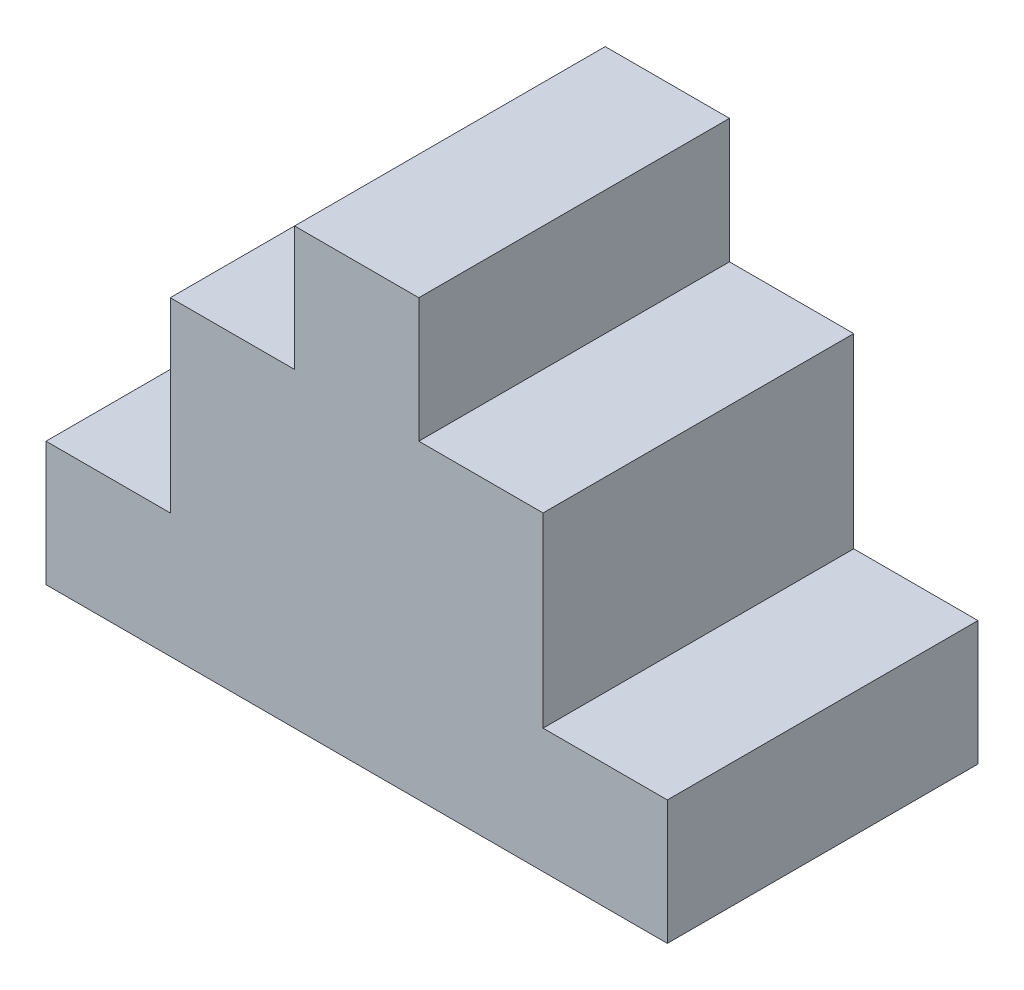
SolidWorks part; units mm, degrees
ref_plane "Front Plane" through (0, 0, 0) normal (0, 0, 1) x (1, 0, 0)
ref_plane "Top Plane" through (0, 0, 0) normal (0, 1, 0) x (1, 0, 0)
ref_plane "Right Plane" through (0, 0, 0) normal (1, 0, 0) x (0, 0, -1)
sketch "Sketch1" plane through (0, 0, 0) normal (0, 0, 1) x (1, 0, 0)
  line L0 (0, 0) -> (0, 2576.0204) construction
  line L1 (0, 0) -> (2576.0204, 0) construction
  line L2 (-1, 7) -> (1, 7)
  line L3 (1, 7) -> (1, 5)
  line L4 (1, 5) -> (3, 5)
  line L5 (3, 5) -> (3, 2)
  line L6 (3, 2) -> (5, 2)
  line L7 (5, 2) -> (5, 0)
  line L8 (5, 0) -> (-5, 0)
  line L9 (-5, 2) -> (-5, 0)
  line L10 (-3, 2) -> (-5, 2)
  line L11 (-3, 5) -> (-3, 2)
  line L12 (-1, 5) -> (-3, 5)
  line L13 (-1, 7) -> (-1, 5)
  point P14 (0, 0)
  point P19 (0, 7)
  dimension "D1" = 2
  dimension "D2" = 2
  dimension "D3" = 3
  dimension "D4" = 2
other "AlignGroup1"
other "AlignGroup2"
extrude "Boss-Extrude1" add sketch "Sketch1" along normal mid plane 5
